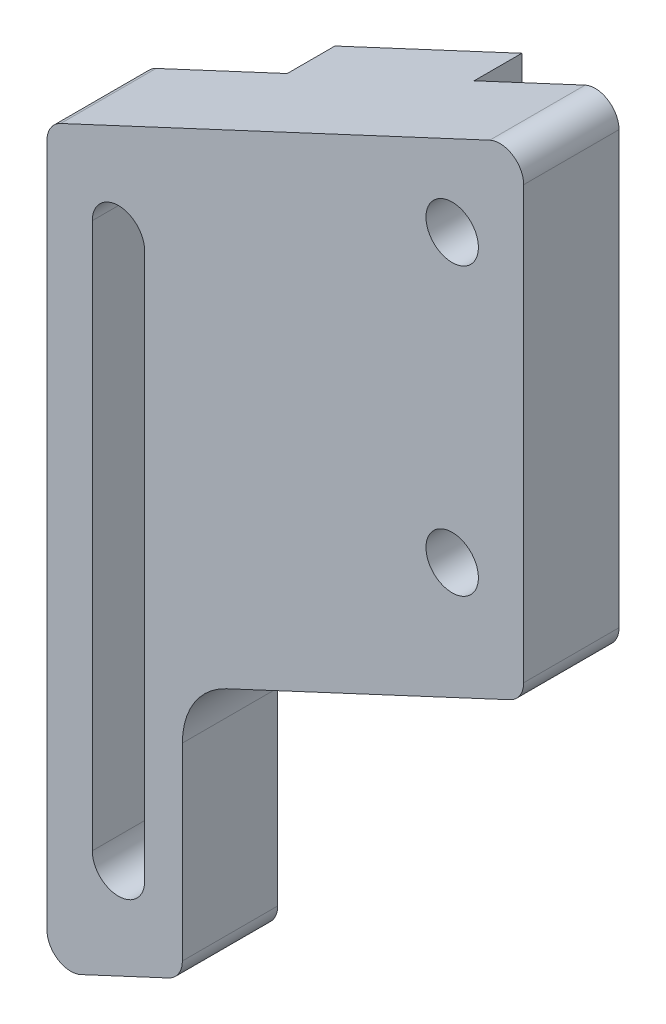
SolidWorks part; units mm, degrees
ref_plane "Front" through (0, 0, 0) normal (0, 0, 1) x (1, 0, 0)
ref_plane "Top" through (0, 0, 0) normal (0, 1, 0) x (1, 0, 0)
ref_plane "Right" through (0, 0, 0) normal (1, 0, 0) x (0, 0, -1)
sketch "Esquisse1" plane through (0, 0, 0) normal (0, 0, 1) x (1, 0, 0)
  line L0 (0, 0) -> (0, 77.2365)
  line L2 (0, 77.2365) -> (50, 100.5518)
  line L3 (50, 100.5518) -> (50, 23.3154)
  line L4 (50, 23.3154) -> (0, 0)
  line L5 (7.5, 80.7338) -> (7.5, 3.4973) construction
  line L6 (7.5, 13.4973) -> (7.5, 70.7338) construction
  line L7 (4.75, 13.4973) -> (4.75, 70.7338)
  line L8 (10.25, 13.4973) -> (10.25, 70.7338)
  arc A0 (4.75, 13.4973) -> (10.25, 13.4973) centre (7.5, 13.4973) ccw
  arc A1 (10.25, 70.7338) -> (4.75, 70.7338) centre (7.5, 70.7338) ccw
  point P11 (7.5, 42.1155)
  dimension "D1" = 65
  dimension "D2" = 70
  dimension "D3" = 7.5
  dimension "D4" = 5.5
  dimension "D5" = 50
  dimension "D6" = 10
  dimension "D7" = 10
extrude "Boss.-Extru.1" add sketch "Esquisse1" along normal blind 15 contours L4 L0 L2 L3
sketch "Esquisse4" plane through (0, 0, 0) normal (0, 0, -1) x (-1, 0, 0)
  line L0 (-15.2, 84.3243) -> (-15.2, 7.0879)
  line L1 (-15.2, 84.3243) -> (-34.8, 93.464)
  line L2 (-15.2, 7.0879) -> (-34.8, 16.2275)
  line L3 (-34.8, 93.464) -> (-34.8, 16.2275)
  line L4 (-50, 100.5518) -> (0, 77.2365) construction
  line L5 (0, 0) -> (-50, 23.3154) construction
  line L6 (0, 77.2365) -> (0, 0) construction
  line L8 (-50, 23.3154) -> (-50, 100.5518) construction
  dimension "D1" = 15.2
  dimension "D2" = 15.2
extrude "Enlèv. mat.-Extru.2" cut sketch "Esquisse4" against normal blind 5 flip side to cut
sketch "Esquisse5" plane through (0, 0, 15) normal (0, 0, 1) x (1, 0, 0)
  line L0 (50, 23.3154) -> (50, 49.7965)
  line L1 (50, 100.5518) -> (0, 77.2365) construction
  line L2 (50, 49.7965) -> (18.8191, 35.2565)
  line L3 (50, 100.5518) -> (0, 77.2365) construction
  line L4 (14.2, 28.0061) -> (14.2, 6.6216)
  line L5 (14.2, 6.6216) -> (50, 23.3154)
  line L7 (0, 0) -> (50, 23.3154) construction
  line L8 (50, 23.3154) -> (50, 100.5518) construction
  line L10 (0, 0) -> (50, 23.3154) construction
  arc A0 (18.8191, 35.2565) -> (14.2, 28.0061) centre (22.2, 28.0061) ccw
  dimension "D3" = 8
  dimension "D1" = 46
  dimension "D2" = 1
extrude "Enlèv. mat.-Extru.3" cut sketch "Esquisse5" against normal through all
sketch "Esquisse6" plane through (0, 0, 0) normal (0, 0, -1) x (-1, 0, 0)
  line L0 (-18.8191, 35.2565) -> (-15.2, 33.5689)
  line L1 (-15.2, 31.8791) -> (-15.2, 84.3243) construction
  line L2 (-15.2, 33.5689) -> (-15.2, 31.8791)
  line L3 (-34.8, 42.7086) -> (-18.8191, 35.2565) construction
  arc A0 (-15.2, 31.8791) -> (-18.8191, 35.2565) centre (-22.2, 28.0061) ccw construction
  arc A1 (-15.2, 31.8791) -> (-18.8191, 35.2565) centre (-22.2, 28.0061) ccw
extrude "Enlèv. mat.-Extru.4" cut sketch "Esquisse6" against normal up to surface (5 mm away) up to face at (9.759, 38.0218, 5)
fillet "Congé1" radius 2.5 5 edges at (0, 0, 10) (0, 77.2365, 10) (50, 100.5518, 10) (14.2, 6.6216, 10) (50, 49.7965, 10)
sketch "Esquisse3" plane through (0, 0, 15) normal (0, 0, 1) x (1, 0, 0)
  line L0 (42.5, 46.2991) -> (42.5, 97.0545) construction
  line L2 (46.4435, 98.8934) -> (1.4435, 77.9095) construction
  line L3 (50, 51.3891) -> (50, 96.6276) construction
  line L4 (48.5565, 49.1234) -> (18.8191, 35.2565) construction
  point P2 (42.5, 88.5545)
  point P9 (42.5, 58.5545)
  dimension "D1" = 7.5
  dimension "D2" = 30
  dimension "D3" = 8.5
hole_wizard "Dégagement M51" positions "Esquisse3D1" profile "Esquisse8" hole size "M5" standard "Ansi Metric" end condition through all
sketch3d "Esquisse3D1"
  point P0 (42.5, 58.5545, 15)
  point P3 (42.5, 88.5545, 15)
sketch "Esquisse8" plane through (42.5, 58.5545, 15) normal (1, 0, 0) x (0, -1, 0)
  line L0 (0, 0) -> (0, 15)
  line L1 (0, 15) -> (2.75, 15)
  line L2 (2.75, 15) -> (2.75, 0)
  line L5 (2.75, 0) -> (0, 0)
  line L11 (0, -6.35) -> (0, 107.95) construction
  dimension "Diamètre du perçage jusqu'au prochain" = 5.5
  dimension "Profondeur du perçage jusqu'au prochain" = 15
sketch "Esquisse10" [suppressed] plane through (0, 0, 15) normal (0, 0, 1) x (1, 0, 0)
  line L0 (2.5, 1.4242) -> (-10, 1.4242)
  line L1 (-10, 1.4242) -> (-10, 72.5734)
  line L2 (-10, 72.5734) -> (1.4435, 77.9095)
  line L3 (46.4435, 98.8934) -> (1.4435, 77.9095) construction
  line L4 (0, 75.6438) -> (0, 3.9242) construction
  line L5 (0, 75.6438) -> (0, 3.9242)
  arc A0 (0, 3.9242) -> (3.5565, 1.6584) centre (2.5, 3.9242) ccw construction
  arc A1 (1.4435, 77.9095) -> (0, 75.6438) centre (2.5, 75.6438) ccw construction
  arc A2 (1.4435, 77.9095) -> (0, 75.6438) centre (2.5, 75.6438) ccw
  arc A3 (0, 3.9242) -> (2.5, 1.4242) centre (2.5, 3.9242) ccw
  dimension "D1" = 10
extrude "Boss.-Extru.2" [suppressed] add sketch "Esquisse10" against normal up to surface (15 mm away)
sketch "Esquisse11" [suppressed] plane through (0, 0, 0) normal (0, 0, -1) x (-1, 0, 0)
  line L0 (0, 3.9242) -> (0, 75.6438) construction
  line L1 (0, 3.9242) -> (0, 75.6438) construction
  line L2 (0.4, 1.4242) -> (0.4, 77.0499)
  line L3 (0.4, 3.9242) -> (0.4, 75.6438) construction
  line L4 (-1.4435, 77.9095) -> (10, 72.5734) construction
  line L5 (10, 1.4242) -> (-2.5, 1.4242) construction
  line L6 (0.4, 1.4242) -> (-2.5, 1.4242)
  line L7 (-1.4435, 77.9095) -> (0.4, 77.0499)
  line L8 (-1.4435, 77.9095) -> (-2.5, 1.4242)
  dimension "D1" = 0.4
extrude "Enlèv. mat.-Extru.5" [suppressed] cut sketch "Esquisse11" against normal up to surface (5 mm away)
fillet "Congé2" [suppressed] radius 2
fillet "Congé3" [suppressed] radius 2.5
ref_plane "Plan1" [suppressed] through (25, 0, 0) normal (-1, 0, 0) x (0, 0, 1)
mirror "Symétrie1" [suppressed] about plane through (25, 0, 0) normal (-1, 0, 0)
delete or keep bodies "Corps-Supprimer/Garder 1" [suppressed] type delete bodies bodies 106
